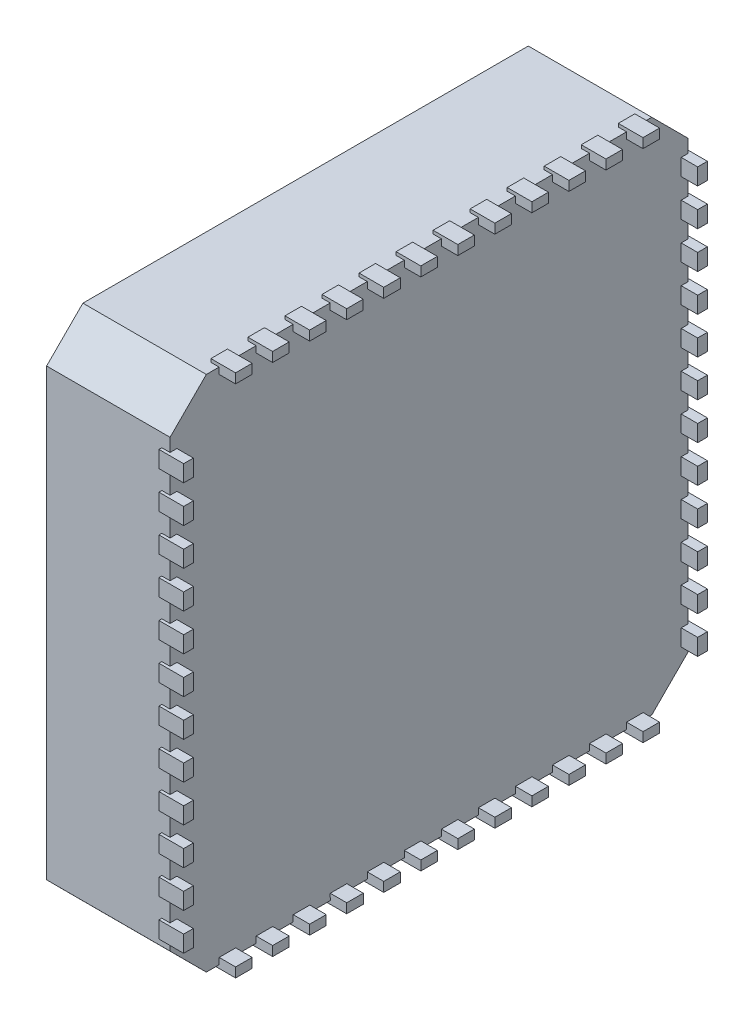
SolidWorks part; units mm, degrees
ref_plane "Front Plane" through (0, 0, 0) normal (0, 0, 1) x (1, 0, 0)
ref_plane "Top Plane" through (0, 0, 0) normal (0, 1, 0) x (1, 0, 0)
ref_plane "Right Plane" through (0, 0, 0) normal (1, 0, 0) x (0, 0, -1)
sketch "Sketch1" plane through (0, 0, 0) normal (1, 0, 0) x (0, 0, -1)
  line L0 (0, -3.1444) -> (0, 3.1556) construction
  line L1 (-2.7057, 3.1444) -> (2.7057, 3.1444)
  line L2 (-3.1466, 2.7035) -> (-3.1466, -2.7032)
  line L3 (-2.7061, -3.1444) -> (2.7061, -3.1444)
  line L4 (3.1466, 2.7035) -> (3.1466, -2.7032)
  line L5 (-2.9238, 2.9263) -> (2.9238, -2.9263) construction
  line L6 (-2.9238, -2.9263) -> (2.9238, 2.9263) construction
  line L7 (3.1466, 2.7035) -> (2.7057, 3.1444)
  line L8 (-2.7061, -3.1444) -> (-3.1466, -2.7032)
  line L9 (-3.1466, 2.7035) -> (-2.7057, 3.1444)
  line L10 (2.7061, -3.1444) -> (3.1466, -2.7032)
  point P0 (0, 0)
extrude "Boss-Extrude1" add sketch "Sketch1" along normal blind 1.5
sketch "Sketch3" plane through (1.5, 0, 0) normal (1, 0, 0) x (0, 0, -1)
  line L0 (-1.8996, 3.1837) -> (-2.1007, 3.1837)
  line L1 (-2.3496, 3.1837) -> (-2.5507, 3.1837)
  line L2 (-2.3496, 3.1837) -> (-2.3496, 3.0673)
  line L3 (-2.3496, 3.0673) -> (-2.5507, 3.0673)
  line L4 (-2.5507, 3.1837) -> (-2.5507, 3.0673)
  line L5 (-1.8996, 3.1837) -> (-1.8996, 3.0673)
  line L6 (-1.8996, 3.0673) -> (-2.1007, 3.0673)
  line L7 (-2.1007, 3.1837) -> (-2.1007, 3.0673)
  line L8 (-1.4496, 3.1837) -> (-1.6507, 3.1837)
  line L9 (-1.4496, 3.1837) -> (-1.4496, 3.0673)
  line L10 (-1.4496, 3.0673) -> (-1.6507, 3.0673)
  line L11 (-1.6507, 3.1837) -> (-1.6507, 3.0673)
  line L12 (-0.9996, 3.1837) -> (-1.2007, 3.1837)
  line L13 (-0.9996, 3.1837) -> (-0.9996, 3.0673)
  line L14 (-0.9996, 3.0673) -> (-1.2007, 3.0673)
  line L15 (-1.2007, 3.1837) -> (-1.2007, 3.0673)
  line L16 (-0.5496, 3.1837) -> (-0.7507, 3.1837)
  line L17 (-0.5496, 3.1837) -> (-0.5496, 3.0673)
  line L18 (-0.5496, 3.0673) -> (-0.7507, 3.0673)
  line L19 (-0.7507, 3.1837) -> (-0.7507, 3.0673)
  line L20 (-0.0996, 3.1837) -> (-0.3007, 3.1837)
  line L21 (-0.0996, 3.1837) -> (-0.0996, 3.0673)
  line L22 (-0.0996, 3.0673) -> (-0.3007, 3.0673)
  line L23 (-0.3007, 3.1837) -> (-0.3007, 3.0673)
  line L24 (0.3504, 3.1837) -> (0.1493, 3.1837)
  line L25 (0.3504, 3.1837) -> (0.3504, 3.0673)
  line L26 (0.3504, 3.0673) -> (0.1493, 3.0673)
  line L27 (0.1493, 3.1837) -> (0.1493, 3.0673)
  line L28 (0.8004, 3.1837) -> (0.5993, 3.1837)
  line L29 (0.8004, 3.1837) -> (0.8004, 3.0673)
  line L30 (0.8004, 3.0673) -> (0.5993, 3.0673)
  line L31 (0.5993, 3.1837) -> (0.5993, 3.0673)
  line L32 (1.2504, 3.1837) -> (1.0493, 3.1837)
  line L33 (1.2504, 3.1837) -> (1.2504, 3.0673)
  line L34 (1.2504, 3.0673) -> (1.0493, 3.0673)
  line L35 (1.0493, 3.1837) -> (1.0493, 3.0673)
  line L36 (1.7004, 3.1837) -> (1.4993, 3.1837)
  line L37 (1.7004, 3.1837) -> (1.7004, 3.0673)
  line L38 (1.7004, 3.0673) -> (1.4993, 3.0673)
  line L39 (1.4993, 3.1837) -> (1.4993, 3.0673)
  line L40 (2.1504, 3.1837) -> (1.9493, 3.1837)
  line L41 (2.1504, 3.1837) -> (2.1504, 3.0673)
  line L42 (2.1504, 3.0673) -> (1.9493, 3.0673)
  line L43 (1.9493, 3.1837) -> (1.9493, 3.0673)
  line L44 (2.6004, 3.1837) -> (2.3993, 3.1837)
  line L45 (2.6004, 3.1837) -> (2.6004, 3.0673)
  line L46 (2.6004, 3.0673) -> (2.3993, 3.0673)
  line L47 (2.3993, 3.1837) -> (2.3993, 3.0673)
  line L48 (-2.3496, 3.1837) -> (-1.8996, 3.1837) construction
  line L49 (0, 0) -> (3.1466, 0.0002) construction
  line L52 (-2.3492, -3.184) -> (-1.8992, -3.1839) construction
  line L53 (2.3996, -3.1834) -> (2.3996, -3.067)
  line L54 (2.6008, -3.067) -> (2.3996, -3.067)
  line L55 (2.6008, -3.1834) -> (2.6008, -3.067)
  line L56 (2.6008, -3.1834) -> (2.3996, -3.1834)
  line L57 (1.9496, -3.1835) -> (1.9496, -3.067)
  line L58 (2.1508, -3.067) -> (1.9496, -3.067)
  line L59 (2.1508, -3.1835) -> (2.1508, -3.067)
  line L60 (2.1508, -3.1835) -> (1.9496, -3.1835)
  line L61 (1.4996, -3.1835) -> (1.4996, -3.0671)
  line L62 (1.7008, -3.0671) -> (1.4996, -3.0671)
  line L63 (1.7008, -3.1835) -> (1.7008, -3.0671)
  line L64 (1.7008, -3.1835) -> (1.4996, -3.1835)
  line L65 (1.0496, -3.1836) -> (1.0496, -3.0671)
  line L66 (1.2508, -3.0671) -> (1.0496, -3.0671)
  line L67 (1.2508, -3.1836) -> (1.2508, -3.0671)
  line L68 (1.2508, -3.1836) -> (1.0496, -3.1836)
  line L69 (0.5996, -3.1837) -> (0.5996, -3.0672)
  line L70 (0.8008, -3.0672) -> (0.5996, -3.0672)
  line L71 (0.8008, -3.1836) -> (0.8008, -3.0672)
  line L72 (0.8008, -3.1836) -> (0.5996, -3.1837)
  line L73 (0.1496, -3.1837) -> (0.1496, -3.0672)
  line L74 (0.3508, -3.0672) -> (0.1496, -3.0672)
  line L75 (0.3508, -3.1837) -> (0.3508, -3.0672)
  line L76 (0.3508, -3.1837) -> (0.1496, -3.1837)
  line L77 (-0.3004, -3.1838) -> (-0.3004, -3.0673)
  line L78 (-0.0992, -3.0673) -> (-0.3004, -3.0673)
  line L79 (-0.0992, -3.1837) -> (-0.0992, -3.0673)
  line L80 (-0.0992, -3.1837) -> (-0.3004, -3.1838)
  line L81 (-0.7504, -3.1838) -> (-0.7504, -3.0673)
  line L82 (-0.5492, -3.0673) -> (-0.7504, -3.0673)
  line L83 (-0.5492, -3.1838) -> (-0.5492, -3.0673)
  line L84 (-0.5492, -3.1838) -> (-0.7504, -3.1838)
  line L85 (-1.2004, -3.1839) -> (-1.2004, -3.0674)
  line L86 (-0.9992, -3.0674) -> (-1.2004, -3.0674)
  line L87 (-0.9992, -3.1838) -> (-0.9992, -3.0674)
  line L88 (-0.9992, -3.1838) -> (-1.2004, -3.1839)
  line L89 (-1.6504, -3.1839) -> (-1.6504, -3.0674)
  line L90 (-1.4492, -3.0674) -> (-1.6504, -3.0674)
  line L91 (-1.4492, -3.1839) -> (-1.4492, -3.0674)
  line L92 (-1.4492, -3.1839) -> (-1.6504, -3.1839)
  line L93 (-2.1004, -3.184) -> (-2.1004, -3.0675)
  line L94 (-1.8992, -3.0675) -> (-2.1004, -3.0675)
  line L95 (-1.8992, -3.1839) -> (-1.8992, -3.0675)
  line L96 (-2.5504, -3.184) -> (-2.5504, -3.0676)
  line L97 (-2.3492, -3.0675) -> (-2.5504, -3.0676)
  line L98 (-2.3492, -3.184) -> (-2.3492, -3.0675)
  line L99 (-2.3492, -3.184) -> (-2.5504, -3.184)
  line L100 (-1.8992, -3.1839) -> (-2.1004, -3.184)
  line L101 (3.1466, -2.7032) -> (3.1466, 2.7035) construction
  line L102 (-2.7057, 3.1444) -> (-2.5507, 3.1444) construction
  line L103 (2.7057, 3.1444) -> (-2.7057, 3.1444) construction
  line L104 (3.1466, 2.7035) -> (3.1466, 2.5435) construction
  line L105 (3.1818, 2.0935) -> (3.1818, 1.8915)
  line L106 (3.1818, 2.5435) -> (3.0634, 2.5435)
  line L107 (3.1818, 2.5435) -> (3.1818, 2.3415)
  line L108 (3.1818, 2.3415) -> (3.0634, 2.3415)
  line L109 (3.0634, 2.5435) -> (3.0634, 2.3415)
  line L110 (3.1818, 2.0935) -> (3.0634, 2.0935)
  line L111 (3.0634, 2.0935) -> (3.0634, 1.8915)
  line L112 (3.1818, 1.8915) -> (3.0634, 1.8915)
  line L113 (3.1818, 1.6435) -> (3.1818, 1.4415)
  line L114 (3.1818, 1.6435) -> (3.0634, 1.6435)
  line L115 (3.0634, 1.6435) -> (3.0634, 1.4415)
  line L116 (3.1818, 1.4415) -> (3.0634, 1.4415)
  line L117 (3.1818, 1.1935) -> (3.1818, 0.9915)
  line L118 (3.1818, 1.1935) -> (3.0634, 1.1935)
  line L119 (3.0634, 1.1935) -> (3.0634, 0.9915)
  line L120 (3.1818, 0.9915) -> (3.0634, 0.9915)
  line L121 (3.1818, 0.7435) -> (3.1818, 0.5415)
  line L122 (3.1818, 0.7435) -> (3.0634, 0.7435)
  line L123 (3.0634, 0.7435) -> (3.0634, 0.5415)
  line L124 (3.1818, 0.5415) -> (3.0634, 0.5415)
  line L125 (3.1818, 0.2935) -> (3.1818, 0.0915)
  line L126 (3.1818, 0.2935) -> (3.0634, 0.2935)
  line L127 (3.0634, 0.2935) -> (3.0634, 0.0915)
  line L128 (3.1818, 0.0915) -> (3.0634, 0.0915)
  line L129 (3.1818, -0.1565) -> (3.1818, -0.3585)
  line L130 (3.1818, -0.1565) -> (3.0634, -0.1565)
  line L131 (3.0634, -0.1565) -> (3.0634, -0.3585)
  line L132 (3.1818, -0.3585) -> (3.0634, -0.3585)
  line L133 (3.1818, -0.6065) -> (3.1818, -0.8085)
  line L134 (3.1818, -0.6065) -> (3.0634, -0.6065)
  line L135 (3.0634, -0.6065) -> (3.0634, -0.8085)
  line L136 (3.1818, -0.8085) -> (3.0634, -0.8085)
  line L137 (3.1818, -1.0565) -> (3.1818, -1.2585)
  line L138 (3.1818, -1.0565) -> (3.0634, -1.0565)
  line L139 (3.0634, -1.0565) -> (3.0634, -1.2585)
  line L140 (3.1818, -1.2585) -> (3.0634, -1.2585)
  line L141 (3.1818, -1.5065) -> (3.1818, -1.7085)
  line L142 (3.1818, -1.5065) -> (3.0634, -1.5065)
  line L143 (3.0634, -1.5065) -> (3.0634, -1.7085)
  line L144 (3.1818, -1.7085) -> (3.0634, -1.7085)
  line L145 (3.1818, -1.9565) -> (3.1818, -2.1585)
  line L146 (3.1818, -1.9565) -> (3.0634, -1.9565)
  line L147 (3.0634, -1.9565) -> (3.0634, -2.1585)
  line L148 (3.1818, -2.1585) -> (3.0634, -2.1585)
  line L149 (3.1818, -2.4065) -> (3.1818, -2.6085)
  line L150 (3.1818, -2.4065) -> (3.0634, -2.4065)
  line L151 (3.0634, -2.4065) -> (3.0634, -2.6085)
  line L152 (3.1818, -2.6085) -> (3.0634, -2.6085)
  line L153 (0, 0) -> (0, -4.6017) construction
  line L154 (-3.1466, 2.7035) -> (-3.1466, 2.5435) construction
  line L155 (0, 0) -> (-3.1466, 0.0002) construction
  line L156 (-3.1818, -2.6085) -> (-3.0634, -2.6085)
  line L157 (-3.0634, -2.4065) -> (-3.0634, -2.6085)
  line L158 (-3.1818, -2.4065) -> (-3.0634, -2.4065)
  line L159 (-3.1818, -2.4065) -> (-3.1818, -2.6085)
  line L160 (-3.1818, -2.1585) -> (-3.0634, -2.1585)
  line L161 (-3.0634, -1.9565) -> (-3.0634, -2.1585)
  line L162 (-3.1818, -1.9565) -> (-3.0634, -1.9565)
  line L163 (-3.1818, -1.9565) -> (-3.1818, -2.1585)
  line L164 (-3.1818, -1.7085) -> (-3.0634, -1.7085)
  line L165 (-3.0634, -1.5065) -> (-3.0634, -1.7085)
  line L166 (-3.1818, -1.5065) -> (-3.0634, -1.5065)
  line L167 (-3.1818, -1.5065) -> (-3.1818, -1.7085)
  line L168 (-3.1818, -1.2585) -> (-3.0634, -1.2585)
  line L169 (-3.0634, -1.0565) -> (-3.0634, -1.2585)
  line L170 (-3.1818, -1.0565) -> (-3.0634, -1.0565)
  line L171 (-3.1818, -1.0565) -> (-3.1818, -1.2585)
  line L172 (-3.1818, -0.8085) -> (-3.0634, -0.8085)
  line L173 (-3.0634, -0.6065) -> (-3.0634, -0.8085)
  line L174 (-3.1818, -0.6065) -> (-3.0634, -0.6065)
  line L175 (-3.1818, -0.6065) -> (-3.1818, -0.8085)
  line L176 (-3.1818, -0.3585) -> (-3.0634, -0.3585)
  line L177 (-3.0634, -0.1565) -> (-3.0634, -0.3585)
  line L178 (-3.1818, -0.1565) -> (-3.0634, -0.1565)
  line L179 (-3.1818, -0.1565) -> (-3.1818, -0.3585)
  line L180 (-3.1818, 0.0915) -> (-3.0634, 0.0915)
  line L181 (-3.0634, 0.2935) -> (-3.0634, 0.0915)
  line L182 (-3.1818, 0.2935) -> (-3.0634, 0.2935)
  line L183 (-3.1818, 0.2935) -> (-3.1818, 0.0915)
  line L184 (-3.1818, 0.5415) -> (-3.0634, 0.5415)
  line L185 (-3.0634, 0.7435) -> (-3.0634, 0.5415)
  line L186 (-3.1818, 0.7435) -> (-3.0634, 0.7435)
  line L187 (-3.1818, 0.7435) -> (-3.1818, 0.5415)
  line L188 (-3.1818, 0.9915) -> (-3.0634, 0.9915)
  line L189 (-3.0634, 1.1935) -> (-3.0634, 0.9915)
  line L190 (-3.1818, 1.1935) -> (-3.0634, 1.1935)
  line L191 (-3.1818, 1.1935) -> (-3.1818, 0.9915)
  line L192 (-3.1818, 1.4415) -> (-3.0634, 1.4415)
  line L193 (-3.0634, 1.6435) -> (-3.0634, 1.4415)
  line L194 (-3.1818, 1.6435) -> (-3.0634, 1.6435)
  line L195 (-3.1818, 1.6435) -> (-3.1818, 1.4415)
  line L196 (-3.1818, 1.8915) -> (-3.0634, 1.8915)
  line L197 (-3.0634, 2.0935) -> (-3.0634, 1.8915)
  line L198 (-3.1818, 2.0935) -> (-3.0634, 2.0935)
  line L199 (-3.0634, 2.5435) -> (-3.0634, 2.3415)
  line L200 (-3.1818, 2.3415) -> (-3.0634, 2.3415)
  line L201 (-3.1818, 2.5435) -> (-3.1818, 2.3415)
  line L202 (-3.1818, 2.5435) -> (-3.0634, 2.5435)
  line L203 (-3.1818, 2.0935) -> (-3.1818, 1.8915)
  dimension "D2" = 0.45
  dimension "D3" = 0.2012
  dimension "D4" = 0.155
  dimension "D5" = 0.16
  dimension "D6" = 0.1165
  dimension "D1" = 12
  dimension "D7" = 12
extrude "Boss-Extrude2" add sketch "Sketch3" along normal blind 0.2 and the other way blind 0.1 separate body
